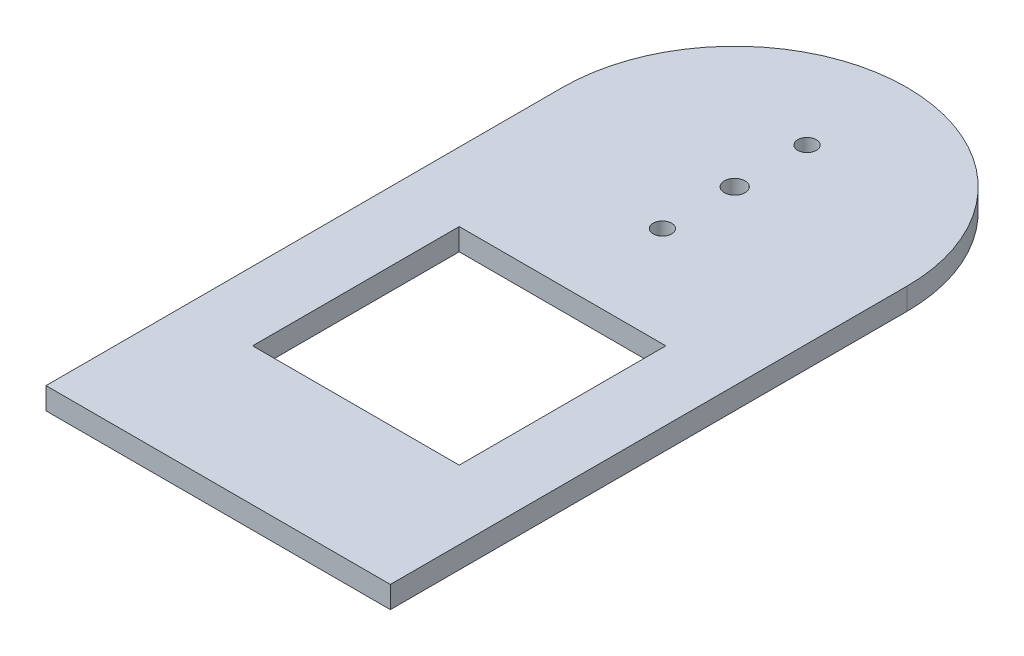
SolidWorks part; units mm, degrees
ref_plane "Front" through (0, 0, 0) normal (0, 0, 1) x (1, 0, 0)
ref_plane "Top" through (0, 0, 0) normal (0, 1, 0) x (1, 0, 0)
ref_plane "Right" through (0, 0, 0) normal (1, 0, 0) x (0, 0, -1)
sketch "Sketch1" plane through (0, 0, 0) normal (0, 1, 0) x (1, 0, 0)
  line L0 (25, 0) -> (25, -100) construction
  line L1 (0, 0) -> (50, 0)
  line L2 (0, 0) -> (0, -100)
  line L3 (0, -100) -> (50, -100)
  line L4 (50, 0) -> (50, -100)
  line L5 (0, -50) -> (50, -50) construction
  line L6 (25, -25) -> (50, -25) construction
  line L8 (10, -50) -> (40, -50)
  line L9 (10, -50) -> (10, -80)
  line L10 (10, -80) -> (40, -80)
  line L11 (40, -50) -> (40, -80)
  circle A0 centre (25, -25) radius 1.5
  circle A1 centre (25, -14.5) radius 1.35
  circle A2 centre (25, -35.5) radius 1.35
  dimension "D3" = 3
  dimension "D4" = 2.7
  dimension "D5" = 10.5
  dimension "D6" = 25
  dimension "D1" = 100
  dimension "D2" = 50
  dimension "D7" = 30
  dimension "D8" = 30
extrude "Boss-Extrude1" add sketch "Sketch1" along normal blind 3.175
sketch "Sketch2" plane through (0, 3.175, 0) normal (0, 1, 0) x (1, 0, 0)
  line L0 (0, -25) -> (0, 0)
  line L1 (0, 0) -> (50, 0)
  line L2 (50, 0) -> (50, -25)
  circle A0 centre (25, -25) radius 25
  line M2 (0, 0) -> (0, -100)
  line M4 (50, -100) -> (50, 0)
  line M5 (50, 0) -> (0, 0)
extrude "Cut-Extrude1" cut sketch "Sketch2" against normal blind 6.35 contours A0 L1 M2 | A0 M4 M5
